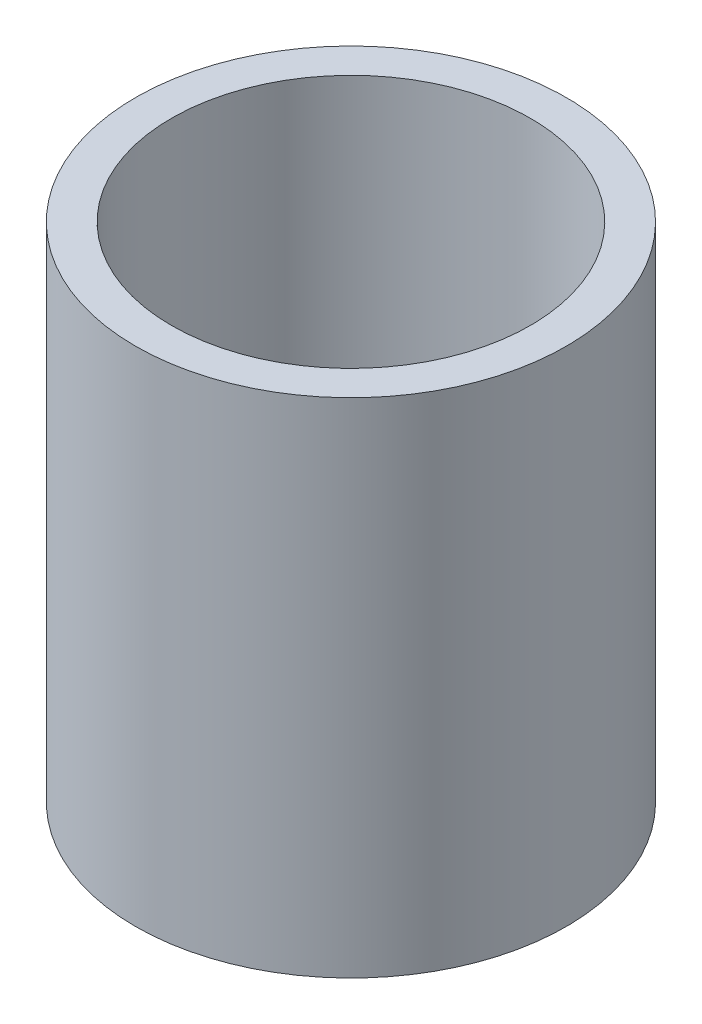
SolidWorks part; units mm, degrees
ref_plane "Front Plane" through (0, 0, 0) normal (0, 0, 1) x (1, 0, 0)
ref_plane "Top Plane" through (0, 0, 0) normal (0, 1, 0) x (1, 0, 0)
ref_plane "Right Plane" through (0, 0, 0) normal (1, 0, 0) x (0, 0, -1)
sketch "Sketch1" plane through (0, 0, 0) normal (0, 1, 0) x (1, 0, 0)
  circle A0 centre (0, 0) radius 76.2
extrude "Boss-Extrude1" add sketch "Sketch1" along normal blind 177.8
shell "Shell1" thickness 12.7
sketch "Sketch2" plane through (0, 12.7, 0) normal (0, 1, 0) x (1, 0, 0)
  text T0 "HI Nicole!\r\nI love you!\r\n\r\n-Steve" font "Century Gothic" height in points 36
extrude "Boss-Extrude2" add sketch "Sketch2" along normal blind 12.7
